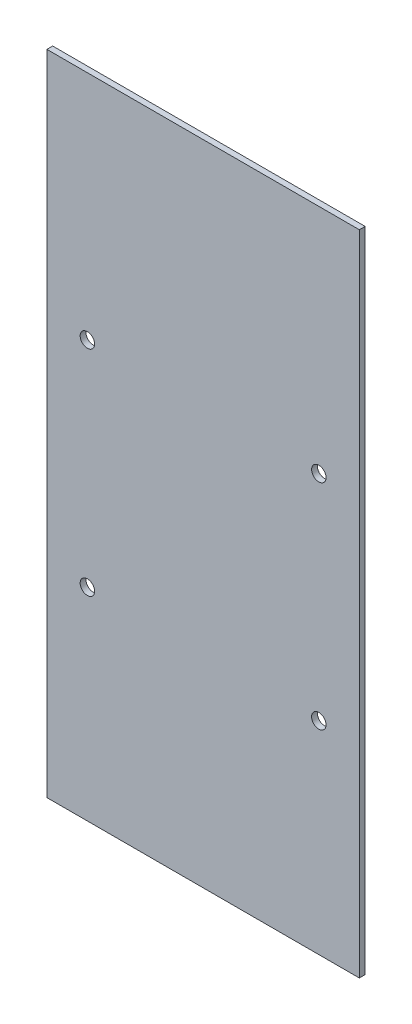
SolidWorks part; units mm, degrees
ref_plane "前视基准面" through (0, 0, 0) normal (0, 0, 1) x (1, 0, 0)
ref_plane "上视基准面" through (0, 0, 0) normal (0, 1, 0) x (1, 0, 0)
ref_plane "右视基准面" through (0, 0, 0) normal (1, 0, 0) x (0, 0, -1)
other "Configuration Table"
sketch "草图1" plane through (0, 0, 0) normal (0, 0, 1) x (1, 0, 0)
  line L0 (0, 73.3392) -> (0, -74.8963) construction
  line L1 (-27, 56) -> (27, 56)
  line L2 (-27, 56) -> (-27, -56)
  line L3 (-27, -56) -> (27, -56)
  line L4 (27, 56) -> (27, -56)
  line L5 (-27, 56) -> (27, -56) construction
  line L6 (-27, -56) -> (27, 56) construction
  circle A8 centre (-20, 16) radius 1.25
  circle A9 centre (-20, -21) radius 1.25
  circle A10 centre (20, -21) radius 1.25
  circle A11 centre (20, 16) radius 1.25
  point P0 (0, 0)
  point P12 (-19.177, -3.7478)
  dimension "D3" = 2.5
  dimension "D4" = 7
  dimension "D5" = 40
  dimension "D6" = 2.5
  dimension "D1" = 54
  dimension "D2" = 112
  dimension "D7" = 7
  dimension "D8" = 35
extrude "凸台-拉伸1" add sketch "草图1" along normal blind 1
